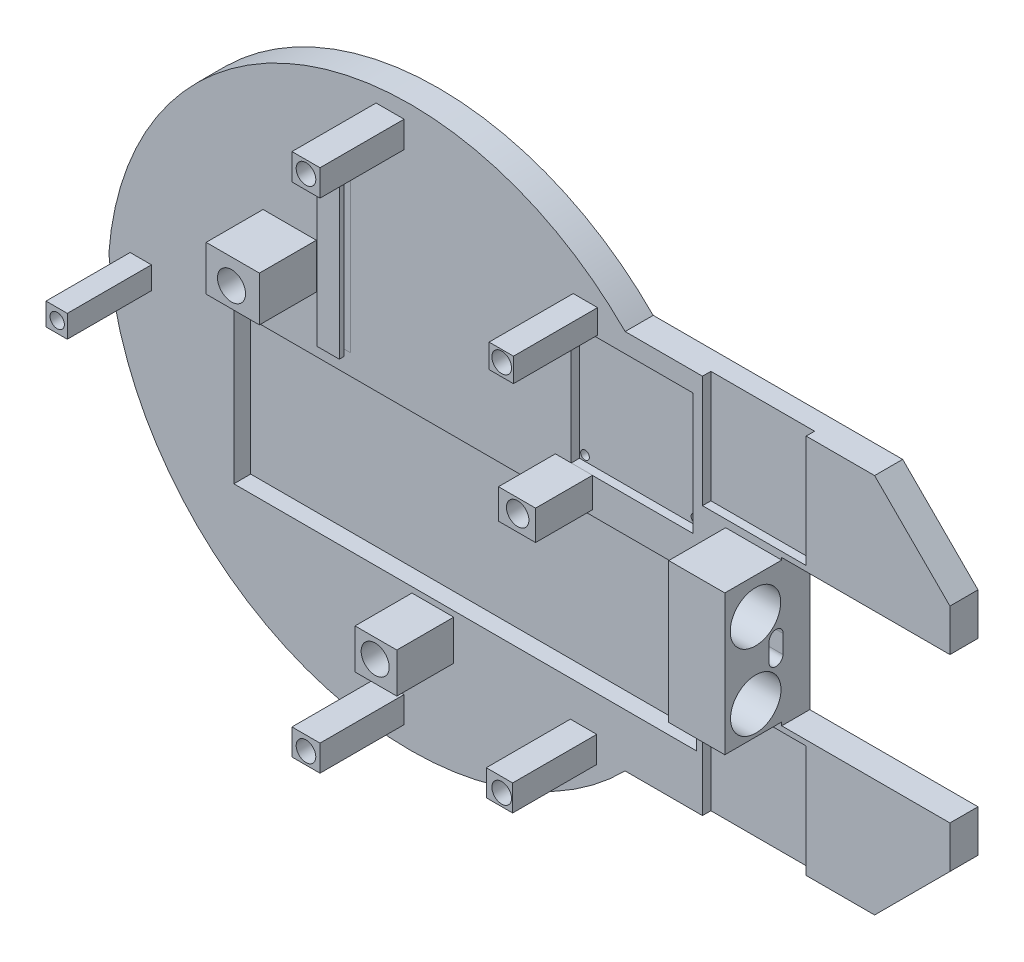
SolidWorks part; units mm, degrees
ref_plane "Front Plane" through (0, 0, 0) normal (0, 0, 1) x (1, 0, 0)
ref_plane "Top Plane" through (0, 0, 0) normal (0, 1, 0) x (1, 0, 0)
ref_plane "Right Plane" through (0, 0, 0) normal (1, 0, 0) x (0, 0, -1)
sketch "Sketch1" plane through (0, 0, 0) normal (0, 0, 1) x (1, 0, 0)
  line L1 (0, 0) -> (0, -26)
  line L2 (0, 26) -> (60, 26)
  line L3 (0, -26) -> (60, -26)
  line L4 (60, 26) -> (60, 41)
  line L5 (60, -26) -> (60, -41)
  line L6 (60, 41) -> (33.1299, 67.8701)
  line L7 (33.1299, 67.8701) -> (-55.8501, 67.8701)
  line L8 (60, -41) -> (33.1299, -67.8701)
  line L9 (33.1299, -67.8701) -> (-55.8501, -67.8701)
  line L10 (-55.8501, 67.8701) -> (-55.8501, 145.9436) construction
  line L11 (-55.8501, 145.9436) -> (-55.8501, -286.005) construction
  line L22 (0, 26) -> (0, 0)
  line L24 (-132.4482, 99.7954) -> (-270.7239, 99.7954) construction
  line L25 (-132.4482, 8.0579) -> (-132.4482, 125.9405) construction
  line L26 (-132.4482, -8.0579) -> (-132.4482, -125.1714) construction
  line L27 (-132.4482, -99.7954) -> (-270.7239, -99.7954) construction
  arc A7 (-240, 0) -> (-55.8501, 67.8701) centre (-132.4482, -8.0579) cw
  arc A8 (-55.8501, -67.8701) -> (-240, 0) centre (-132.4482, 8.0579) cw
  dimension "D11" = 199.5908
  dimension "D12" = 240
  dimension "D10" = 135.7401
  dimension "D1" = 26
  dimension "D2" = 26
  dimension "D3" = 60
  dimension "D4" = 15
  dimension "D5" = 15
  dimension "D6" = 135
  dimension "D7" = 38
  dimension "D8" = 38
  dimension "D9" = 135
  dimension "D15" = 88.98
  dimension "D16" = 88.98
extrude "Boss-Extrude1" add sketch "Sketch1" along normal blind 10 and the other way blind 0.01
sketch "Sketch3" plane through (0, 0, 10) normal (0, 0, 1) x (1, 0, 0)
  line L0 (33.1299, 67.8701) -> (-55.8501, 67.8701) construction
  line L1 (-28.273, 67.8701) -> (8.727, 67.8701)
  line L2 (-28.273, 67.8701) -> (-28.273, 27.8701)
  line L3 (-28.273, 27.8701) -> (8.727, 27.8701)
  line L4 (8.727, 67.8701) -> (8.727, 27.8701)
  dimension "D1" = 40
  dimension "D2" = 37
extrude "Cut-Extrude1" cut sketch "Sketch3" against normal blind 3 contours L2 L1 L4 L3
sketch "Sketch5" plane through (0, 0, 10) normal (0, 0, 1) x (1, 0, 0)
  line L0 (-55.8501, -67.8701) -> (33.1299, -67.8701) construction
  line L1 (-28.273, -27.8701) -> (8.727, -27.8701)
  line L2 (-28.273, -27.8701) -> (-28.273, -67.8701)
  line L3 (-28.273, -67.8701) -> (8.727, -67.8701)
  line L4 (8.727, -27.8701) -> (8.727, -67.8701)
extrude "Cut-Extrude3" cut sketch "Sketch5" against normal blind 3
sketch "Sketch7" plane through (0, 0, 10) normal (0, 0, 1) x (1, 0, 0)
  line L1 (-195.4131, 5.0562) -> (-30.4131, 5.0562)
  line L2 (-195.4131, 5.0562) -> (-195.4131, -48.9438)
  line L3 (-195.4131, -48.9438) -> (-30.4131, -48.9438)
  line L4 (-30.4131, 5.0562) -> (-30.4131, -48.9438)
  dimension "D1" = 54
  dimension "D2" = 165
extrude "Cut-Extrude4" cut sketch "Sketch7" against normal blind 6
sketch "Sketch8" plane through (0, 0, 10) normal (0, 0, 1) x (1, 0, 0)
  line L1 (-162.9927, 67.8133) -> (-84.7927, 67.8133)
  line L2 (-162.9927, 67.8133) -> (-162.9927, 10.3133)
  line L3 (-162.9927, 10.3133) -> (-84.7927, 10.3133)
  line L4 (-84.7927, 67.8133) -> (-84.7927, 10.3133)
  dimension "D1" = 78.2
  dimension "D2" = 57.5
extrude "Cut-Extrude5" [suppressed] cut sketch "Sketch8" against normal blind 3
sketch "Sketch9" plane through (0, 0, 10) normal (0, 0, 1) x (1, 0, 0)
  line L1 (-185, 41) -> (-166, 41)
  line L2 (-185, 41) -> (-185, 25)
  line L3 (-185, 25) -> (-166, 25)
  line L4 (-166, 41) -> (-166, 25)
  line L5 (-80.7317, 17.6542) -> (-67.493, 17.6542)
  line L6 (-80.7317, 17.6542) -> (-80.7317, 7.0108)
  line L7 (-80.7317, 7.0108) -> (-67.493, 7.0108)
  line L8 (-67.493, 17.6542) -> (-67.493, 7.0108)
  line L9 (-131.8867, -50.9252) -> (-116.9909, -50.9252)
  line L10 (-131.8867, -50.9252) -> (-131.8867, -65.1638)
  line L11 (-131.8867, -65.1638) -> (-116.9909, -65.1638)
  line L12 (-116.9909, -50.9252) -> (-116.9909, -65.1638)
  point P12 (0, 0)
extrude "Boss-Extrude2" add sketch "Sketch9" along normal blind 20.3
sketch "Sketch15" plane through (0, 0, 10) normal (0, 0, 1) x (1, 0, 0)
  line L0 (0, -26) -> (0, 26) construction
  line L1 (-20, 25.2016) -> (0, 25.2016)
  line L2 (-20, 25.2016) -> (-20, -24.7984)
  line L3 (-20, -24.7984) -> (0, -24.7984)
  line L4 (0, 25.2016) -> (0, -24.7984)
  dimension "D1" = 50
  dimension "D2" = 20
extrude "Boss-Extrude3" add sketch "Sketch15" along normal blind 20.3
sketch "Sketch4" plane through (0, 0, 7) normal (0, 0, 1) x (1, 0, 0)
  line L1 (-28.3661, -27.8728) -> (8.6339, -27.8728)
  line L2 (-28.3661, -27.8728) -> (-28.3661, -67.8728)
  line L3 (-28.3661, -67.8728) -> (8.6339, -67.8728)
  line L4 (8.6339, -27.8728) -> (8.6339, -67.8728)
  dimension "D1" = 40
  dimension "D2" = 37
sketch "Sketch16" plane through (0, 0, 10) normal (0, 0, 1) x (1, 0, 0)
  line L1 (-232.4208, 4) -> (-224.8235, 4)
  line L2 (-232.4208, 4) -> (-232.4208, -4)
  line L3 (-232.4208, -4) -> (-224.8235, -4)
  line L4 (-224.8235, 4) -> (-224.8235, -4)
  line L9 (-134.6881, 94.0493) -> (-144.6881, 94.0493)
  line L10 (-134.6881, 94.0493) -> (-134.6881, 84.6493)
  line L11 (-134.6881, 84.6493) -> (-144.6881, 84.6493)
  line L12 (-144.6881, 94.0493) -> (-144.6881, 84.6493)
  line L13 (-65.6779, 70.3488) -> (-74.3779, 70.3488)
  line L14 (-65.6779, 70.3488) -> (-65.6779, 61.8488)
  line L15 (-65.6779, 61.8488) -> (-74.3779, 61.8488)
  line L16 (-74.3779, 70.3488) -> (-74.3779, 61.8488)
  line L17 (-65.9779, -61.6233) -> (-75.3779, -61.6233)
  line L18 (-65.9779, -61.6233) -> (-65.9779, -70.9233)
  line L19 (-65.9779, -70.9233) -> (-75.3779, -70.9233)
  line L20 (-75.3779, -61.6233) -> (-75.3779, -70.9233)
  line L21 (-134.6881, -83.6815) -> (-144.6881, -83.6815)
  line L22 (-134.6881, -83.6815) -> (-134.6881, -92.9815)
  line L23 (-134.6881, -92.9815) -> (-144.6881, -92.9815)
  line L24 (-144.6881, -83.6815) -> (-144.6881, -92.9815)
extrude "Boss-Extrude4" add sketch "Sketch16" along normal blind 30
sketch "Sketch17" plane through (0, 0, 0) normal (0, 0, 1) x (1, 0, 0)
  circle A1 centre (-228.4208, 0) radius 2.55
  circle A2 centre (-139.6881, 89.6493) radius 3.5
  circle A3 centre (-69.8779, 66.3488) radius 3.5
  circle A4 centre (-69.8779, -66.6233) radius 3.5
  circle A5 centre (-139.6881, -88.6815) radius 3.5
extrude "Cut-Extrude17" cut sketch "Sketch17" along normal through all
sketch "Sketch18" plane through (0, 0, 10) normal (0, 0, 1) x (1, 0, 0)
  line L1 (-75.1245, 61) -> (-31.7245, 61)
  line L2 (-75.1245, 61) -> (-75.1245, 17.6)
  line L3 (-75.1245, 17.6) -> (-31.7245, 17.6)
  line L4 (-31.7245, 61) -> (-31.7245, 17.6)
  dimension "D1" = 43.4
  dimension "43.4" = 43.4
extrude "Cut-Extrude18" cut sketch "Sketch18" against normal blind 3
sketch "Sketch20" plane through (0, 0, 0) normal (0, 0, 1) x (1, 0, 0)
  circle A0 centre (-175.9471, 32.1121) radius 5
  circle A1 centre (-124.7094, -57.6129) radius 5
  circle A2 centre (-73.8879, 12.7504) radius 4
extrude "Cut-Extrude20" cut sketch "Sketch20" along normal through all
sketch "Sketch21" plane through (0, 0, 0) normal (1, 0, 0) x (0, 0, -1)
  line L0 (-3.8276, 29.0855) -> (-3.8276, -37.1575) construction
  line L1 (-6.4886, 28.3852) -> (-6.4886, -37.2976) construction
  line L2 (-5.0881, 28.1051) -> (-5.0881, -37.5777) construction
  line L3 (-11.99, 2.3019) -> (-12.0559, -4.1532) construction
  line L4 (-9.4916, 2.2764) -> (-9.5574, -4.1787)
  line L5 (-14.4885, 2.3274) -> (-14.5544, -4.1277)
  circle A0 centre (-19.3619, 12.3718) radius 9
  circle A1 centre (-19.2654, -14.6282) radius 9
  arc A2 (-9.4916, 2.2764) -> (-14.4885, 2.3274) centre (-11.99, 2.3019) ccw
  arc A3 (-14.5544, -4.1277) -> (-9.5574, -4.1787) centre (-12.0559, -4.1532) ccw
  point P12 (-12.023, -0.9256)
  dimension "D1" = 18
  dimension "D2" = 18
  dimension "D3" = 27
extrude "Cut-Extrude21" cut sketch "Sketch21" against normal up to surface (20 mm away) up to face at (-20, 0.2016, 20.15)
sketch "Sketch22" plane through (0, 0, 7) normal (0, 0, 1) x (1, 0, 0)
  circle A0 centre (-73.1686, 58.9795) radius 1.55
  circle A1 centre (-33.7686, 58.9795) radius 1.55
  circle A2 centre (-33.7686, 19.5795) radius 1.55
  circle A3 centre (-73.1686, 19.5795) radius 1.55
  point P3 (0, 0)
  point P4 (0, 0)
  dimension "D1" = 2
  dimension "D2" = 2
extrude "Cut-Extrude23" cut sketch "Sketch22" against normal through all
sketch "Sketch25" plane through (0, 0, 10) normal (0, 0, 1) x (1, 0, 0)
  line L1 (-161.6964, 70.8495) -> (-153.7964, 70.8495)
  line L2 (-161.6964, 70.8495) -> (-161.6964, 12.3495)
  line L3 (-161.6964, 12.3495) -> (-153.7964, 12.3495)
  line L4 (-153.7964, 70.8495) -> (-153.7964, 12.3495)
  point P4 (0, 0)
  point P5 (0, 0)
  dimension "D1" = 7.9
  dimension "D2" = 58.5
extrude "Boss-Extrude5" add sketch "Sketch25" along normal blind 4
sketch "Sketch26" plane through (0, 12.3495, 0) normal (0, -1, 0) x (1, 0, 0)
  line L0 (-161.679, 10.0037) -> (-152.674, 9.9893) construction
  line L1 (-152.674, 9.9893) -> (-152.6595, 14.6073) construction
  line L2 (-153.7928, 10.0085) -> (-161.6128, 10.0085)
  line L3 (-161.6128, 10.0085) -> (-161.6128, 12.4083)
  line L4 (-161.6128, 12.4083) -> (-153.7928, 12.4083)
  line L5 (-153.7928, 12.4083) -> (-153.7928, 10.0083)
  line M7 (-153.7964, 10) -> (-153.7964, 14)
extrude "Cut-Extrude24" cut sketch "Sketch26" against normal up to surface (58.5 mm away) contours L4 L3 L2 M7 up to face at (-157.7464, 70.8495, 12)
